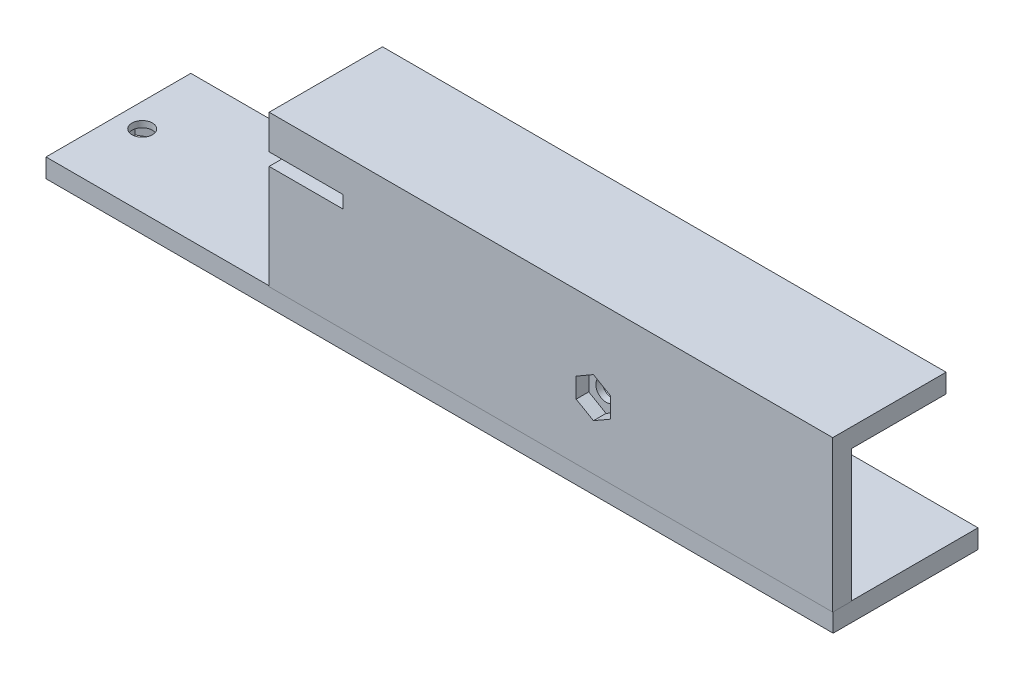
SolidWorks part; units mm, degrees
ref_plane "Alzado" through (0, 0, 0) normal (0, 0, 1) x (1, 0, 0)
ref_plane "Planta" through (0, 0, 0) normal (0, 1, 0) x (1, 0, 0)
ref_plane "Vista lateral" through (0, 0, 0) normal (1, 0, 0) x (0, 0, -1)
sketch "Croquis1" plane through (0, 0, 0) normal (0, 0, 1) x (1, 0, 0)
  line L0 (7.541, -2.6917) -> (7.541, -13.1917) construction
  line L1 (7.541, -13.1917) -> (45.541, -13.1917)
  line L2 (45.541, -13.1917) -> (45.541, 7.8083)
  line L3 (45.541, 7.8083) -> (-30.459, 7.8083)
  line L4 (-30.459, 7.8083) -> (-30.459, -13.1917)
  line L5 (-30.459, -13.1917) -> (7.541, -13.1917)
  circle A0 centre (7.541, -2.6917) radius 1.625
  dimension "D5" = 3.25
  dimension "D1" = 7.541
  dimension "D2" = 45.541
  dimension "D3" = 7.8083
  dimension "D4" = 13.1917
  dimension "D6" = 2.6917
extrude "Saliente-Extruir1" add sketch "Croquis1" along normal blind 3
sketch "Croquis2" plane through (0, 0, 3) normal (0, 0, 1) x (1, 0, 0)
  line L0 (7.541, -2.6917) -> (7.541, -13.1917) construction
  line L1 (-30.459, -13.1917) -> (45.541, -13.1917) construction
  line L3 (7.541, 0.4783) -> (4.7957, -1.1067)
  line L4 (4.7957, -1.1067) -> (4.7957, -4.2767)
  line L5 (4.7957, -4.2767) -> (7.541, -5.8617)
  line L6 (7.541, -5.8617) -> (10.2863, -4.2767)
  line L7 (10.2863, -4.2767) -> (10.2863, -1.1067)
  line L8 (10.2863, -1.1067) -> (7.541, 0.4783)
  line L9 (45.541, 7.8083) -> (-30.459, 7.8083) construction
  circle A1 centre (7.541, -2.6917) radius 2.7453 construction
  dimension "D1" = 5.4906
  dimension "D2" = 7.33
extrude "Cortar-Extruir1" cut sketch "Croquis2" against normal blind 2
sketch "Croquis3" plane through (0, -13.1917, 0) normal (0, -1, 0) x (1, 0, 0)
  line L7 (53.041, -14.5) -> (-37.8534, -14.5) construction
  line L9 (2.041, -20) -> (2.041, -14.5) construction
  line L10 (-79.5254, 2.8672) -> (45.4746, 2.8672)
  line L11 (45.4746, -20.1328) -> (-79.5254, -20.1328)
  line L13 (45.4746, -20.1328) -> (45.4746, 2.8672)
  line L14 (45.541, 3) -> (45.541, 0) construction
  line L15 (-30.459, 0) -> (45.541, 0) construction
  line L16 (-79.5254, 2.8672) -> (-79.5254, -20.1328)
  line L17 (-47.889, -8.6328) -> (-47.889, -20.1328) construction
  line L18 (-75.749, -8.6328) -> (-75.749, -20.1328) construction
  circle A0 centre (2.041, -14.5) radius 1.625
  circle A1 centre (-37.8534, -14.5) radius 1.625
  circle A2 centre (-75.749, -8.6328) radius 1.625
  circle A3 centre (-47.889, -8.6328) radius 1.625
  dimension "D4" = 83.3945
  dimension "D1" = 3.25
  dimension "D2" = 0.0664
  dimension "D3" = 43.5
  dimension "D5" = 93.43
  dimension "D6" = 121.29
  dimension "D7" = 125.0664
  dimension "D8" = 2.8672
  dimension "D9" = 8.6328
  dimension "D10" = 14.5
  dimension "D11" = 20.1328
extrude "Saliente-Extruir2" add sketch "Croquis3" along normal blind 3
sketch "Croquis4" plane through (0, 7.8083, 0) normal (0, 1, 0) x (1, 0, 0)
  line L0 (45.541, -3) -> (-30.459, -3)
  line L1 (45.541, -3) -> (45.541, 0) construction
  line L4 (-30.459, -3) -> (-30.459, 12)
  line L5 (45.541, -3) -> (45.541, 12)
  line L6 (45.541, 12) -> (-30.459, 12)
  line L7 (-30.459, -3) -> (-30.459, 0) construction
  line L9 (45.541, 0) -> (-30.459, 0) construction
  dimension "D1" = 12
  dimension "D2" = 3
extrude "Saliente-Extruir3" add sketch "Croquis4" along normal blind 3
sketch "Croquis14" plane through (-30.459, 0, 0) normal (-1, 0, 0) x (0, 0, 1)
  line L0 (-12, 10.8083) -> (3, 10.8083)
  line L1 (3, 10.8083) -> (3, -13.1917)
  line L2 (3, -13.1917) -> (0, -13.1917)
  line L3 (0, -13.1917) -> (0, 7.8083)
  line L4 (0, 7.8083) -> (-12, 7.8083)
  line L5 (-12, 7.8083) -> (-12, 10.8083)
  line L6 (3, 10.8083) -> (3, -13.1917) construction
  line L7 (2.8672, -13.1917) -> (0, -13.1917) construction
  dimension "D1" = 3
  dimension "D2" = 15
  dimension "D3" = 21
extrude "Saliente-Extruir5" add sketch "Croquis14" along normal blind 13.5
sketch "Croquis18" plane through (0, 0, -12) normal (0, 0, -1) x (-1, 0, 0)
  line L0 (43.959, 10.8083) -> (43.959, -1.1917)
  line L1 (43.959, 7.8083) -> (43.959, -13.1917) construction
  line L2 (43.959, -1.1917) -> (30.959, -1.1917)
  line L3 (30.959, -1.1917) -> (30.959, 10.8083)
  line L4 (30.959, 10.8083) -> (43.959, 10.8083)
  line L5 (43.959, 10.8083) -> (43.959, 7.8083) construction
  line L6 (-45.541, 7.8083) -> (43.959, 7.8083) construction
  dimension "D1" = 13
  dimension "D2" = 9
extrude "Saliente-Extruir6" add sketch "Croquis18" along normal blind 3
sketch "Croquis19" plane through (0, 0, -15) normal (0, 0, -1) x (-1, 0, 0)
  line L0 (37.3401, 7.3583) -> (43.959, 7.3583)
  line L1 (43.959, -1.1917) -> (43.959, 10.8083) construction
  line L2 (37.3401, 1.3583) -> (43.959, 1.3583)
  line L3 (43.959, 7.3583) -> (43.959, 1.3583)
  arc A0 (37.3401, 7.3583) -> (37.3401, 1.3583) centre (37.3102, 4.3583) ccw
  arc A1 (34.382, 3.8583) -> (34.382, 4.8583) centre (37.3401, 4.3583) ccw construction
  dimension "D1" = 3.0001
extrude "Cortar-Extruir6" cut sketch "Croquis19" against normal blind 3
sketch "Croquis21" plane through (0, 10.8083, 0) normal (0, 1, 0) x (1, 0, 0)
  line L1 (45.541, 12) -> (-30.959, 12)
  line L2 (45.541, 12) -> (45.541, 15)
  line L3 (45.541, 15) -> (-30.959, 15)
  line L4 (-30.959, 12) -> (-30.959, 15)
extrude "Saliente-Extruir7" add sketch "Croquis21" against normal blind 3
sketch "Croquis23" plane through (0, 0, 3) normal (0, 0, 1) x (1, 0, 0)
  line L0 (-43.959, 5.3583) -> (-43.959, 3.3583)
  line L1 (-43.959, -13.1917) -> (-43.959, 10.8083) construction
  line L2 (4.7957, -1.1067) -> (4.7957, -4.2767) construction
  line L3 (-43.959, 5.3583) -> (-32.1968, 5.3583)
  line L4 (-43.959, 10.8083) -> (45.541, 10.8083) construction
  line L6 (-32.1968, 5.3583) -> (-32.1968, 3.3583)
  line L7 (-32.1968, 3.3583) -> (-43.959, 3.3583)
  dimension "D1" = 36.9925
  dimension "D2" = 5.45
  dimension "D3" = 7.45
extrude "Cortar-Extruir7" cut sketch "Croquis23" against normal blind 3
sketch "Croquis24" plane through (0, -13.1917, 0) normal (0, 1, 0) x (1, 0, 0)
  line L0 (-43.959, 0) -> (-43.959, -2.8672) construction
  circle A0 centre (2.041, 14.5) radius 3.36
  circle A1 centre (-37.8534, 14.5) radius 3.36
  dimension "D1" = 6.7199
  dimension "D2" = 6.7199
  dimension "D3" = 6.1055
  dimension "D4" = 46
  dimension "D5" = 14.5
extrude "Cortar-Extruir8" cut sketch "Croquis24" against normal blind 1.8 draft 44
sketch "Croquis25" plane through (0, -16.1917, 0) normal (0, -1, 0) x (1, 0, 0)
  line L0 (-75.749, -8.6328) -> (-79.5254, -8.6328) construction
  line L1 (-79.5254, 2.8672) -> (-79.5254, -20.1328) construction
  line L2 (-47.923, -8.574) -> (-47.923, -20.1328) construction
  line L3 (-79.5254, -20.1328) -> (45.4746, -20.1328) construction
  line L4 (45.4746, 2.8672) -> (-79.5254, 2.8672) construction
  line L5 (-47.923, -5.404) -> (-50.6683, -6.989)
  line L6 (-50.6683, -6.989) -> (-50.6683, -10.159)
  line L7 (-50.6683, -10.159) -> (-47.923, -11.744)
  line L8 (-47.923, -11.744) -> (-45.1777, -10.159)
  line L9 (-45.1777, -10.159) -> (-45.1777, -6.989)
  line L10 (-45.1777, -6.989) -> (-47.923, -5.404)
  line L11 (-75.749, -5.4628) -> (-78.4943, -7.0478)
  line L12 (-78.4943, -7.0478) -> (-78.4943, -10.2178)
  line L13 (-78.4943, -10.2178) -> (-75.749, -11.8028)
  line L14 (-75.749, -11.8028) -> (-73.0037, -10.2178)
  line L15 (-73.0037, -10.2178) -> (-73.0037, -7.0478)
  line L16 (-73.0037, -7.0478) -> (-75.749, -5.4628)
  circle A0 centre (-47.923, -8.574) radius 2.7453 construction
  circle A1 centre (-75.749, -8.6328) radius 2.7453 construction
  dimension "D1" = 5.4906
  dimension "D2" = 1.0311
  dimension "D3" = 28.8571
  dimension "D4" = 8.2711
extrude "Cortar-Extruir9" cut sketch "Croquis25" against normal blind 2
